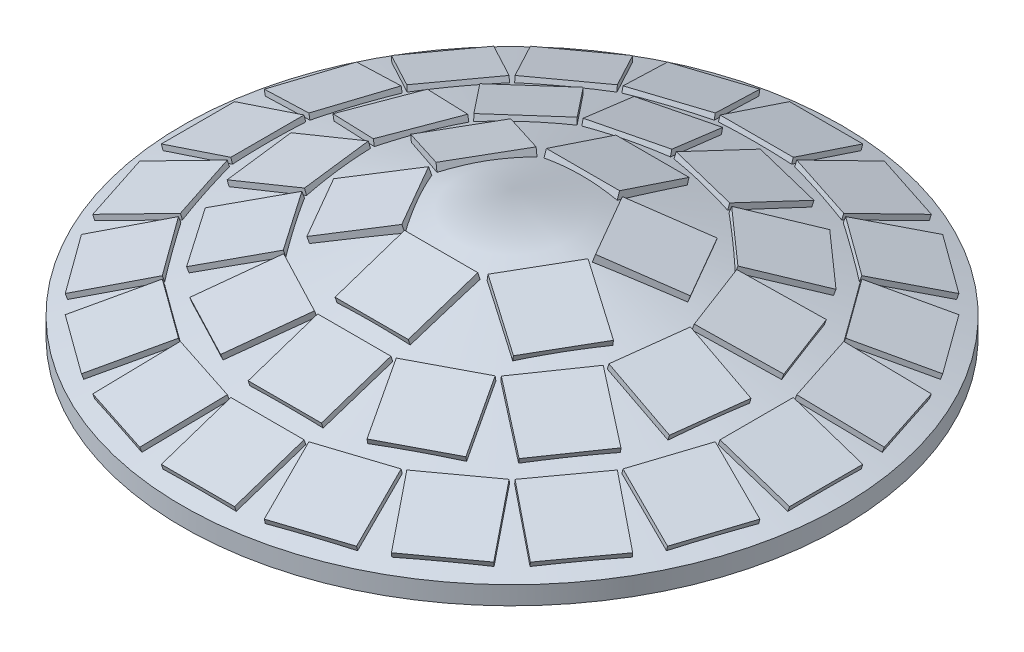
SolidWorks part; units mm, degrees
ref_plane "Frontal Plane" through (0, 0, 0) normal (0, 0, 1) x (1, 0, 0)
ref_plane "Horizontal Plane" through (0, 0, 0) normal (0, 1, 0) x (1, 0, 0)
ref_plane "Profile Plane" through (0, 0, 0) normal (1, 0, 0) x (0, 0, -1)
sketch "Sketch1" plane through (0, 0, 0) normal (0, 0, 1) x (1, 0, 0)
  line L2 (-457.2, 25.4) -> (0, 177.8)
  line L3 (0, 177.8) -> (0, 152.4)
  line L4 (0, 152.4) -> (-457.2, 0)
  line L5 (-457.2, 0) -> (-457.2, 25.4)
  line L6 (0, 0) -> (0, 146.6057) construction
  dimension "D1" = 25.4
  dimension "D2" = 457.2
  dimension "D3" = 152.4
revolve "Revolve1" add sketch "Sketch1" angle 360 about L6
sketch "Sketch2" plane through (0, 0, 0) normal (0, 1, 0) x (1, 0, 0)
  line L1 (63.5, -63.5) -> (-63.5, -63.5)
  line L2 (63.5, -63.5) -> (63.5, 63.5)
  line L3 (63.5, 63.5) -> (-63.5, 63.5)
  line L4 (-63.5, -63.5) -> (-63.5, 63.5)
  line L5 (63.5, -63.5) -> (-63.5, 63.5) construction
  line L6 (63.5, 63.5) -> (-63.5, -63.5) construction
  point P0 (0, 0)
  dimension "D1" = 127
  dimension "D2" = 127
extrude "Boss-Extrude1" add sketch "Sketch2" along normal blind 50.8 and the other way blind 127 separate body
sketch "Sketch3" plane through (0, -127, 0) normal (0, -1, 0) x (1, 0, 0)
  line L1 (51.435, -51.435) -> (-51.435, -51.435)
  line L2 (51.435, -51.435) -> (51.435, 51.435)
  line L3 (51.435, 51.435) -> (-51.435, 51.435)
  line L4 (-51.435, -51.435) -> (-51.435, 51.435)
  line L5 (51.435, -51.435) -> (-51.435, 51.435) construction
  line L6 (51.435, 51.435) -> (-51.435, -51.435) construction
  point P0 (0, 0)
  dimension "D1" = 102.87
  dimension "D2" = 102.87
extrude "Cut-Extrude1" cut sketch "Sketch3" against normal blind 127
sketch "Sketch4" plane through (63.5, 0, 0) normal (1, 0, 0) x (0, 0, -1)
  line L0 (-63.5, -127) -> (63.5, -127) construction
  line L1 (-63.5, 50.8) -> (-63.5, -127) construction
  line L2 (63.5, 50.8) -> (63.5, -127) construction
  circle A0 centre (-31.75, -63.5) radius 3.175
  circle A1 centre (31.75, -63.5) radius 3.175
  point P4 (0, 0)
  dimension "D4" = 6.35
  dimension "D1" = 63.5
  dimension "D2" = 31.75
  dimension "D3" = 31.75
extrude "Cut-Extrude2" cut sketch "Sketch4" against normal up to surface (127 mm away) up to face at (-63.5, -38.1, 0)
sketch "Sketch5" plane through (0, 0, 63.5) normal (0, 0, 1) x (1, 0, 0)
  line L0 (-63.5, 50.8) -> (-63.5, -127) construction
  line L1 (-63.5, -127) -> (63.5, -127) construction
  line L2 (63.5, 50.8) -> (63.5, -127) construction
  circle A0 centre (-31.75, -50.8) radius 3.175
  circle A1 centre (31.75, -50.8) radius 3.175
  dimension "D1" = 6.35
  dimension "D2" = 31.75
  dimension "D3" = 76.2
  dimension "D4" = 31.75
extrude "Cut-Extrude3" cut sketch "Sketch5" against normal up to surface (127 mm away) up to face at (0, -38.1, -63.5)
surface "Surface-Plane4"
sketch "Sketch10" plane through (0, 25.4, 0) normal (0, -1, 0) x (-1, 0, 0)
  line L0 (0, -457.2) -> (0, 0)
  circle A0 centre (0, 0) radius 457.2 construction
  point P5 (0, 0)
ref_plane "Plane1" through (0, 25.4, 457.2) normal (0, 0.9487, 0.3162) x (1, 0, 0)
sketch "Sketch11" plane through (0, 25.4, 457.2) normal (0, 0.9487, 0.3162) x (1, 0, 0)
  line L1 (-50.8, 24.7311) -> (50.8, 24.7311)
  line L2 (-50.8, 24.7311) -> (-50.8, 126.3311)
  line L3 (-50.8, 126.3311) -> (50.8, 126.3311)
  line L4 (50.8, 24.7311) -> (50.8, 126.3311)
  line L5 (-50.8, 24.7311) -> (50.8, 126.3311) construction
  line L6 (-50.8, 126.3311) -> (50.8, 24.7311) construction
  point P0 (0, 75.5311)
  point P5 (0, 24.7311)
  point P6 (0, 126.3311)
  dimension "D1" = 101.6
  dimension "D2" = 101.6
  dimension "D3" = 406.4
extrude "Boss-Extrude5" add sketch "Sketch11" along normal blind 6.35 and the other way offset from surface (6.35 mm away) 6.35
pattern_circular "CirPattern11" count 20 over 360 about axis through (0, 0, 0) along (0, 1, 0) of "Boss-Extrude5"
sketch "Sketch12" plane through (0, 25.4, 457.2) normal (0, 0.9487, 0.3162) x (1, 0, 0)
  line L1 (-50.8, 253.3311) -> (50.8, 253.3311)
  line L2 (-50.8, 253.3311) -> (-50.8, 151.7311)
  line L3 (-50.8, 151.7311) -> (50.8, 151.7311)
  line L4 (50.8, 253.3311) -> (50.8, 151.7311)
  line L5 (-50.8, 253.3311) -> (50.8, 151.7311) construction
  line L6 (-50.8, 151.7311) -> (50.8, 253.3311) construction
  point P0 (0, 202.5311)
  point P7 (0, 151.7311)
  point P9 (0, 253.3311)
  dimension "D1" = 101.6
  dimension "D2" = 101.6
  dimension "D3" = 279.4
extrude "Boss-Extrude6" add sketch "Sketch12" along normal blind 6.35 and the other way up to surface (6.35 mm away)
pattern_circular "CirPattern12" count 13 over 360 about axis through (0, 0, 0) along (0, 1, 0) of "Boss-Extrude6"
sketch "Sketch13" plane through (0, 25.4, 457.2) normal (0, 0.9487, 0.3162) x (1, 0, 0)
  line L1 (-50.8, 380.3311) -> (50.8, 380.3311)
  line L2 (-50.8, 380.3311) -> (-50.8, 278.7311)
  line L3 (-50.8, 278.7311) -> (50.8, 278.7311)
  line L4 (50.8, 380.3311) -> (50.8, 278.7311)
  line L5 (-50.8, 380.3311) -> (50.8, 278.7311) construction
  line L6 (-50.8, 278.7311) -> (50.8, 380.3311) construction
  point P0 (0, 329.5311)
  point P5 (0, 278.7311)
  point P6 (0, 380.3311)
  dimension "D1" = 101.6
  dimension "D2" = 101.6
  dimension "D3" = 152.4
extrude "Boss-Extrude7" add sketch "Sketch13" along normal blind 6.35 and the other way up to surface (6.35 mm away)
pattern_circular "CirPattern13" count 6 over 360 about axis through (0, 0, 0) along (0, 1, 0) of "Boss-Extrude7"
